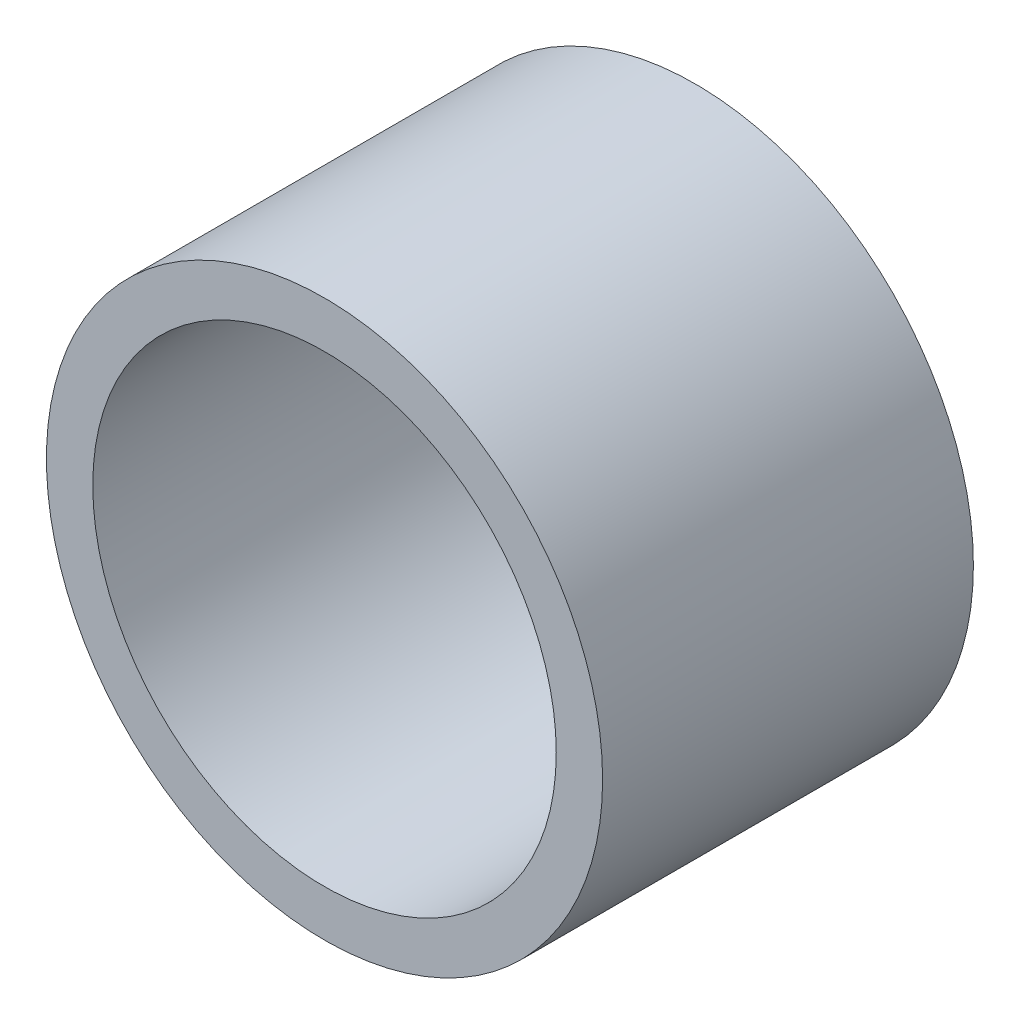
SolidWorks part; units mm, degrees
ref_plane "前视基准面" through (0, 0, 0) normal (0, 0, 1) x (1, 0, 0)
ref_plane "上视基准面" through (0, 0, 0) normal (0, 1, 0) x (1, 0, 0)
ref_plane "右视基准面" through (0, 0, 0) normal (1, 0, 0) x (0, 0, -1)
sketch "草图1" plane through (0, 0, 0) normal (0, 0, 1) x (1, 0, 0)
  circle A0 centre (0, 0) radius 5
  circle A1 centre (0, 0) radius 6
extrude "凸台-拉伸1" add sketch "草图1" along normal blind 8
